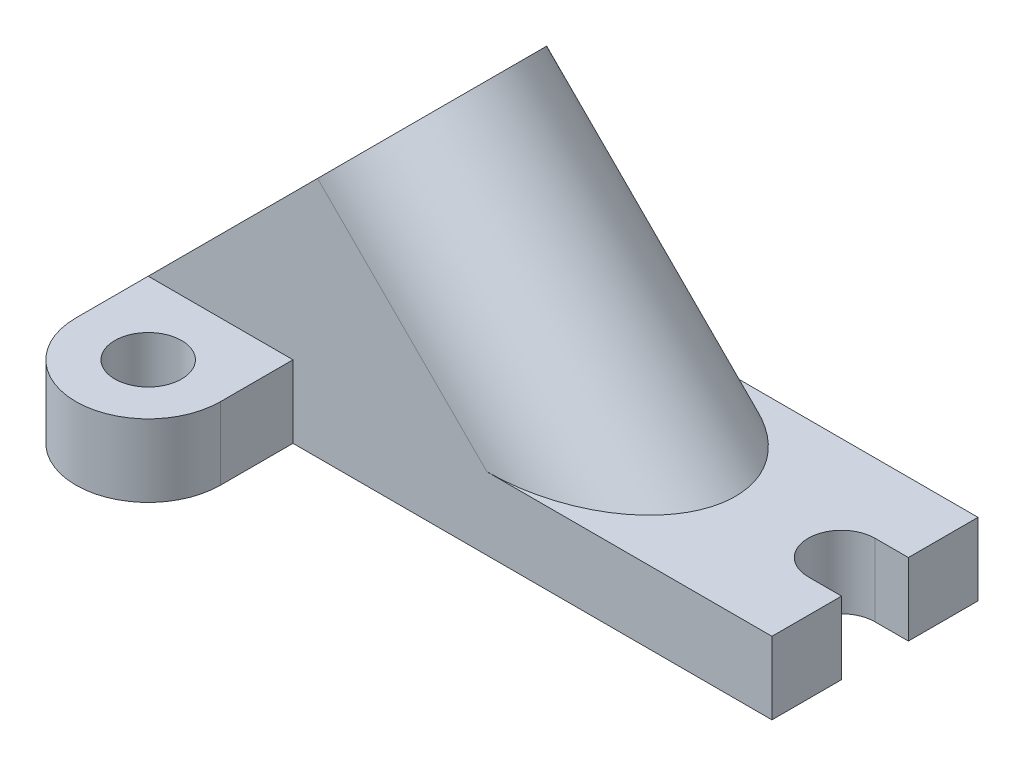
SolidWorks part; units mm, degrees
ref_plane "Front Plane" through (0, 0, 0) normal (0, 0, 1) x (1, 0, 0)
ref_plane "Top Plane" through (0, 0, 0) normal (0, 1, 0) x (1, 0, 0)
ref_plane "Right Plane" through (0, 0, 0) normal (1, 0, 0) x (0, 0, -1)
sketch "Sketch1" plane through (0, 0, 0) normal (0, 1, 0) x (1, 0, 0)
  line L0 (0, 31.5) -> (0, -31.5) construction
  line L1 (13, 31.5) -> (13, -31.5)
  line L2 (-13, 31.5) -> (-13, -31.5)
  arc A0 (13, 31.5) -> (-13, 31.5) centre (0, 31.5) ccw
  arc A1 (-13, -31.5) -> (13, -31.5) centre (0, -31.5) ccw
  circle A2 centre (0, 31.5) radius 6
  circle A3 centre (0, -31.5) radius 6
  point P3 (0, 0)
  dimension "D2" = 13
  dimension "D3" = 12
  dimension "D4" = 12
  dimension "D1" = 63
extrude "Boss-Extrude1" add sketch "Sketch1" along normal blind 13
sketch "Sketch2" plane through (0, 0, 0) normal (0, 0, 1) x (1, 0, 0)
  line L0 (13, 0) -> (99, 0)
  line L1 (99, 0) -> (99, 13)
  line L2 (99, 13) -> (13, 13)
  line L4 (13, 13) -> (13, 0) construction
  line L5 (13, 13) -> (-13, 13) construction
  line L6 (13, 13) -> (13, 0)
  dimension "D1" = 13
  dimension "D2" = 112
extrude "Boss-Extrude2" add sketch "Sketch2" along normal mid plane 37 contours L2 L6 L0 L1
sketch "Sketch3" plane through (0, 13, 0) normal (0, 1, 0) x (1, 0, 0)
  line L0 (0, 0) -> (99, 0) construction
  line L1 (99, -18.5) -> (99, 18.5) construction
  line L2 (105, 0) -> (93, 0) construction
  line L3 (105, -6) -> (93, -6)
  line L4 (105, 6) -> (93, 6)
  arc A0 (105, -6) -> (105, 6) centre (105, 0) ccw
  arc A1 (93, 6) -> (93, -6) centre (93, 0) ccw
  point P7 (99, 0)
  dimension "D2" = 6
  dimension "D1" = 12
extrude "Cut-Extrude1" cut sketch "Sketch3" against normal blind 37
ref_plane "Plane1" through (-13, 13, 0) normal (-0.7071, 0.7071, 0) x (0, 0, 1)
sketch "Sketch4" plane through (-13, 13, 0) normal (-0.7071, 0.7071, 0) x (0, 0, 1)
  line L0 (-31.5, 0) -> (31.5, 0) construction
  line L2 (-18.5, 43) -> (-18.5, 0)
  line L3 (18.5, 43) -> (18.5, 0)
  line L4 (18.5, 0) -> (-18.5, 0)
  line L5 (0, 43) -> (0, 0) construction
  circle A0 centre (0, 43) radius 8
  arc A1 (18.5, 43) -> (-18.5, 43) centre (0, 43) ccw
  dimension "D2" = 16
  dimension "D3" = 18.5
  dimension "D1" = 43
extrude "Boss-Extrude3" add sketch "Sketch4" against normal blind 64
sketch "Sketch6" plane through (0, 0, 0) normal (0, 0, 1) x (1, 0, 0)
  line L0 (99, 0) -> (99, 13) construction
  line L1 (-13, 0) -> (99, 0)
  line L2 (-13, 0) -> (-13, -33.3937)
  line L3 (-13, -33.3937) -> (99, -33.3937)
  line L4 (99, 0) -> (99, -33.3937)
  dimension "D1" = 33.3937
extrude "Cut-Extrude2" cut sketch "Sketch6" against normal mid plane 64
sketch "Sketch7" plane through (-13, 13, 0) normal (-0.7071, 0.7071, 0) x (0, 0, 1)
  circle A0 centre (0, 43) radius 8
  dimension "D1" = 16
extrude "Cut-Extrude3" cut sketch "Sketch7" against normal blind 88
